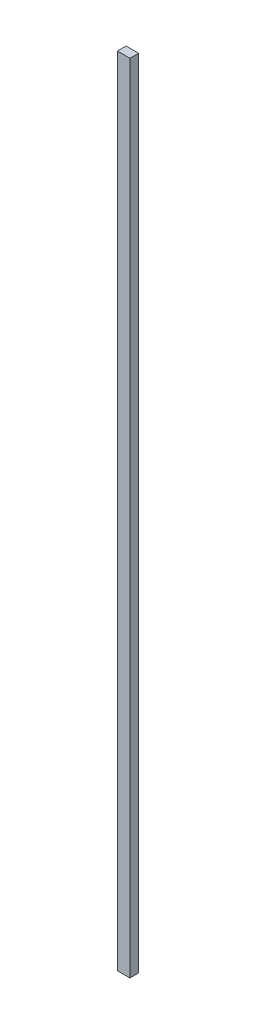
SolidWorks part; units mm, degrees
ref_plane "Front Plane" through (0, 0, 0) normal (0, 0, 1) x (1, 0, 0)
ref_plane "Top Plane" through (0, 0, 0) normal (0, 1, 0) x (1, 0, 0)
ref_plane "Right Plane" through (0, 0, 0) normal (1, 0, 0) x (0, 0, -1)
sketch "Sketch1" plane through (0, 0, 0) normal (0, 1, 0) x (1, 0, 0)
  line L1 (-13.7884, 13.5968) -> (-15.2051, 13.5968)
  line L2 (-13.7884, 13.5968) -> (-13.7884, 12.62)
  line L3 (-13.7884, 12.62) -> (-15.2051, 12.62)
  line L4 (-15.2051, 13.5968) -> (-15.2051, 12.62)
extrude "Boss-Extrude1" add sketch "Sketch1" along normal blind 89.916
